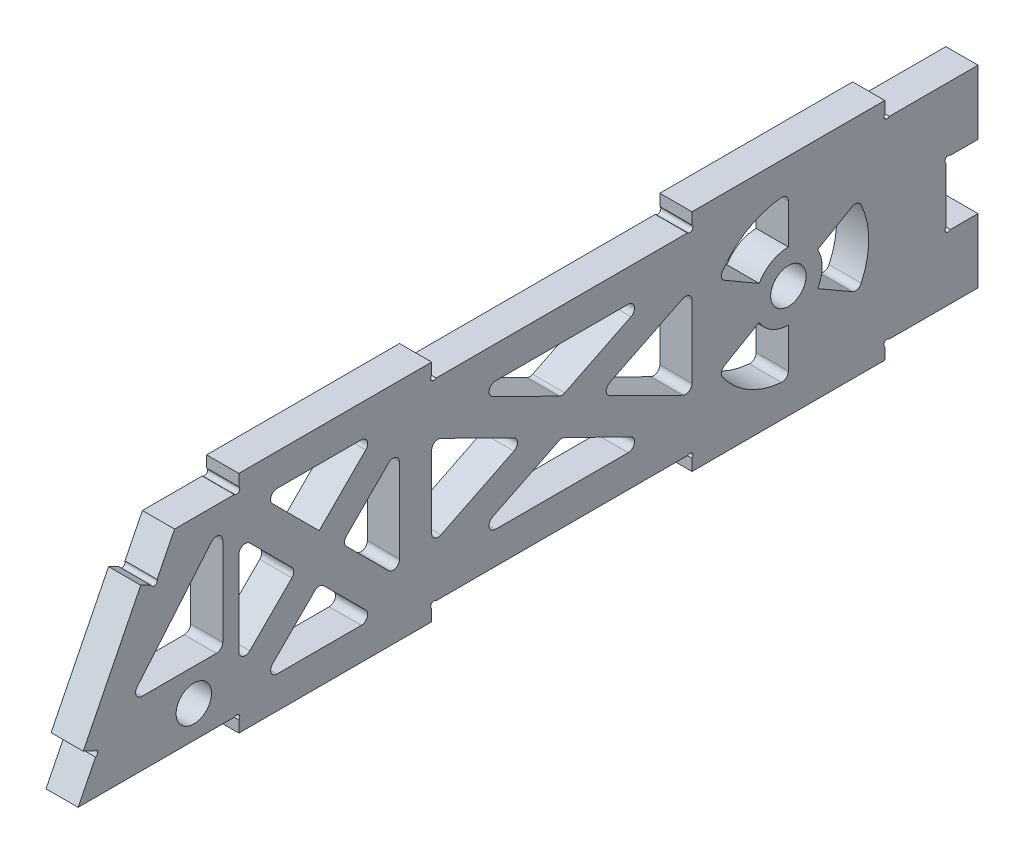
SolidWorks part; units mm, degrees
material "7050-T73510"
ref_plane "Front Plane" through (0, 0, 0) normal (0, 0, 1) x (1, 0, 0)
ref_plane "Top Plane" through (0, 0, 0) normal (0, 1, 0) x (1, 0, 0)
ref_plane "Right Plane" through (0, 0, 0) normal (1, 0, 0) x (0, 0, -1)
sketch "Sketch1" plane through (0, 0, 0) normal (1, 0, 0) x (0, 0, -1)
  line L1 (-177.8, -38.1) -> (177.8, -38.1)
  line L2 (-177.8, -38.1) -> (-177.8, 38.1)
  line L3 (-177.8, 38.1) -> (177.8, 38.1)
  line L4 (177.8, -38.1) -> (177.8, 38.1)
  line L5 (-177.8, -38.1) -> (177.8, 38.1) construction
  line L6 (-177.8, 38.1) -> (177.8, -38.1) construction
  point P0 (0, 0)
  dimension "D1" = 355.6
  dimension "D2" = 76.2
extrude "Boss-Extrude1" add sketch "Sketch1" along normal blind 12.7
sketch "Sketch2" plane through (12.7, 0, 0) normal (1, 0, 0) x (0, 0, -1)
  line L0 (-177.8, -38.1) -> (-139.7, 38.1)
  line L1 (177.8, 38.1) -> (-177.8, 38.1) construction
  dimension "D1" = 38.1
extrude "Cut-Extrude1" cut sketch "Sketch2" against normal through all and the other way through all
sketch "Sketch3" plane through (0, 0, 0) normal (-1, 0, 0) x (0, 0, 1)
  line L0 (177.8, -38.1) -> (-177.8, -38.1) construction
  line L1 (-140.97, -38.1) -> (-64.77, -38.1)
  line L2 (-140.97, -38.1) -> (-140.97, -44.45)
  line L3 (-140.97, -44.45) -> (-64.77, -44.45)
  line L4 (-64.77, -38.1) -> (-64.77, -44.45)
  line L5 (-177.8, -38.1) -> (-177.8, 38.1) construction
  line L6 (38.1, -38.1) -> (114.3, -38.1)
  line L7 (38.1, -38.1) -> (38.1, -44.45)
  line L8 (38.1, -44.45) -> (114.3, -44.45)
  line L9 (114.3, -38.1) -> (114.3, -44.45)
  line L10 (-177.8, 38.1) -> (139.7, 38.1) construction
  line L11 (-140.97, 38.1) -> (-64.77, 38.1)
  line L12 (-140.97, 38.1) -> (-140.97, 44.45)
  line L13 (-140.97, 44.45) -> (-64.77, 44.45)
  line L14 (-64.77, 38.1) -> (-64.77, 44.45)
  line L16 (38.1, 38.1) -> (114.3, 38.1)
  line L17 (38.1, 38.1) -> (38.1, 44.45)
  line L18 (38.1, 44.45) -> (114.3, 44.45)
  line L19 (114.3, 38.1) -> (114.3, 44.45)
  dimension "D1" = 76.2
  dimension "D2" = 6.35
  dimension "D3" = 76.2
  dimension "D4" = 6.35
  dimension "D5" = 36.83
  dimension "D6" = 215.9
  dimension "D7" = 76.2
  dimension "D8" = 6.35
  dimension "D9" = 6.35
  dimension "D10" = 76.2
extrude "Boss-Extrude2" add sketch "Sketch3" against normal blind 12.7
sketch "Sketch4" plane through (0, 0, 0) normal (-1, 0, 0) x (0, 0, 1)
  line L0 (-177.8, -38.1) -> (-177.8, 38.1) construction
  line L1 (-177.8, 12.7) -> (-165.1, 12.7)
  line L2 (-177.8, 12.7) -> (-177.8, -12.7)
  line L3 (-177.8, -12.7) -> (-165.1, -12.7)
  line L4 (-165.1, 12.7) -> (-165.1, -12.7)
  line L5 (-140.97, -38.1) -> (-177.8, -38.1) construction
  line L6 (-177.8, 38.1) -> (-140.97, 38.1) construction
  dimension "D1" = 25.4
  dimension "D2" = 25.4
  dimension "D3" = 12.7
extrude "Cut-Extrude2" cut sketch "Sketch4" against normal through all
sketch "Sketch5" plane through (0, 0, 0) normal (-1, 0, 0) x (0, 0, 1)
  line L0 (-165.1, -12.7) -> (-165.1, 12.7) construction
  line L1 (-140.97, -38.1) -> (-177.8, -38.1) construction
  circle A0 centre (-102.87, 0) radius 7
  dimension "D1" = 62.23
  dimension "D3" = 14
  dimension "D2" = 38.1
extrude "Cut-Extrude3" cut sketch "Sketch5" against normal through all
sketch "Sketch6" plane through (0, 0, 0) normal (-1, 0, 0) x (0, 0, 1)
  line L0 (38.1, -38.1) -> (-64.77, -38.1) construction
  line L1 (-64.77, 25.4) -> (38.1, 25.4)
  line L2 (-64.77, 25.4) -> (-64.77, -25.4)
  line L3 (-64.77, -25.4) -> (38.1, -25.4)
  line L4 (38.1, 25.4) -> (38.1, -25.4)
  line L5 (-64.77, 38.1) -> (38.1, 38.1) construction
  line L6 (38.1, 44.45) -> (38.1, 38.1) construction
  line L7 (-64.77, 38.1) -> (-64.77, 44.45) construction
  line L8 (-64.77, 25.4) -> (38.1, -25.4) construction
  line L9 (-64.77, -25.4) -> (38.1, 25.4) construction
  line L10 (-50.4288, -25.4) -> (-13.335, -7.0821)
  line L11 (23.7588, 25.4) -> (-13.335, 7.0821)
  line L12 (-50.4288, 25.4) -> (-13.335, 7.0821)
  line L13 (23.7588, -25.4) -> (-13.335, -7.0821)
  line L14 (1.0062, 0) -> (38.1, 18.3179)
  line L15 (-27.6762, 0) -> (-64.77, 18.3179)
  line L16 (1.0062, 0) -> (38.1, -18.3179)
  line L17 (-27.6762, 0) -> (-64.77, -18.3179)
  line L18 (38.1, -44.45) -> (114.3, -44.45) construction
  line L19 (50.8, 31.75) -> (114.3, 31.75)
  line L20 (50.8, 31.75) -> (50.8, -31.75)
  line L21 (50.8, -31.75) -> (114.3, -31.75)
  line L22 (114.3, 31.75) -> (114.3, -31.75)
  line L23 (114.3, 44.45) -> (38.1, 44.45) construction
  line L26 (114.3, 38.1) -> (114.3, 44.45) construction
  line L28 (50.8, -31.75) -> (114.3, 31.75) construction
  line L29 (114.3, -31.75) -> (50.8, 31.75) construction
  line L30 (59.7803, -31.75) -> (114.3, 22.7697)
  line L31 (50.8, -22.7697) -> (105.3197, 31.75)
  line L32 (114.3, -22.7697) -> (59.7803, 31.75)
  line L33 (105.3197, -31.75) -> (50.8, 22.7697)
  point P36 (114.3, 41.275)
  dimension "D1" = 12.7
  dimension "D2" = 12.7
  dimension "D3" = 12.7
  dimension "D4" = 12.7
  dimension "D5" = 12.7
  dimension "D6" = 12.7
  dimension "D7" = 12.7
  dimension "D8" = 0
  dimension "D9" = 12.7
  dimension "D10" = 12.7
extrude "Cut-Extrude4" cut sketch "Sketch6" against normal through all contours L3 L13 L10 | L17 L15 L2 | L1 L12 L11 | L14 L16 L4 | L21 L33 L30 | L32 L22 L30 | L31 L33 L20 | L32 L31 L19
sketch "Sketch8" plane through (12.7, 0, 0) normal (1, 0, 0) x (0, 0, -1)
  line L0 (-147.3908, 22.7185) -> (-170.1092, -22.7185)
  line L1 (-147.3908, 22.7185) -> (-153.0704, 25.5583)
  line L2 (-170.1092, -22.7185) -> (-175.7888, -19.8786)
  line L3 (-153.0704, 25.5583) -> (-175.7888, -19.8786)
  line L4 (-177.8, -38.1) -> (-139.7, 38.1) construction
  line L5 (-158.75, 0) -> (-181.9472, 11.5986) construction
  dimension "D1" = 6.35
  dimension "D2" = 50.8
extrude "Boss-Extrude3" add sketch "Sketch8" against normal blind 12.7
sketch "Sketch9" plane through (0, 0, 0) normal (-1, 0, 0) x (0, 0, 1)
  line L0 (147.3908, 22.7185) -> (147.7924, 23.9233) construction
  line L1 (170.1092, -22.7185) -> (172.0432, -23.3631) construction
  line L2 (147.3908, 22.7185) -> (153.0704, 25.5583) construction
  line L3 (175.7888, -19.8786) -> (170.1092, -22.7185) construction
  line L4 (-140.97, 38.1) -> (-141.868, 38.998) construction
  line L5 (37.202, -38.998) -> (38.1, -38.1) construction
  line L6 (38.1, -38.1) -> (-64.77, -38.1) construction
  line L7 (-63.872, -38.998) -> (-64.77, -38.1) construction
  line L8 (-141.868, -38.998) -> (-140.97, -38.1) construction
  line L9 (-140.97, -38.1) -> (-177.8, -38.1) construction
  line L10 (-165.998, -11.802) -> (-165.1, -12.7) construction
  line L11 (-165.1, -12.7) -> (-165.1, 12.7) construction
  line L12 (-165.998, 11.802) -> (-165.1, 12.7) construction
  line L13 (-165.1, 12.7) -> (-177.8, 12.7) construction
  line L14 (-140.97, 44.45) -> (-140.97, 38.1) construction
  line L15 (-63.872, 38.998) -> (-64.77, 38.1) construction
  line L16 (-64.77, 38.1) -> (-64.77, 44.45) construction
  line L17 (37.202, 38.998) -> (38.1, 38.1) construction
  line L18 (38.1, 44.45) -> (38.1, 38.1) construction
  line L19 (114.3, 38.1) -> (115.198, 38.998) construction
  line L20 (114.3, 38.1) -> (114.3, 44.45) construction
  line L21 (115.198, -38.998) -> (114.3, -38.1) construction
  line L22 (114.3, -44.45) -> (114.3, -38.1) construction
  circle A0 centre (-165.998, 11.802) radius 1.27
  circle A1 centre (-165.998, -11.802) radius 1.27
  circle A2 centre (-141.868, 38.998) radius 1.27
  circle A3 centre (-141.868, -38.998) radius 1.27
  circle A4 centre (-63.872, -38.998) radius 1.27
  circle A5 centre (-63.872, 38.998) radius 1.27
  circle A6 centre (37.202, 38.998) radius 1.27
  circle A7 centre (37.202, -38.998) radius 1.27
  circle A8 centre (115.198, -38.998) radius 1.27
  circle A9 centre (115.198, 38.998) radius 1.27
  circle A10 centre (147.7924, 23.9233) radius 1.27
  circle A11 centre (171.3141, -23.1201) radius 1.27
  dimension "D1" = 45
  dimension "D3" = 1.27
  dimension "D2" = 45
  dimension "D4" = 45
  dimension "D5" = 1.27
  dimension "D6" = 45
  dimension "D7" = 1.27
  dimension "D8" = 45
  dimension "D9" = 1.27
  dimension "D10" = 45
  dimension "D11" = 1.27
  dimension "D12" = 45
  dimension "D13" = 1.27
  dimension "D14" = 45
  dimension "D15" = 45
  dimension "D16" = 1.27
  dimension "D17" = 1.27
  dimension "D18" = 45
  dimension "D19" = 1.27
  dimension "D20" = 45
  dimension "D21" = 1.27
  dimension "D22" = 1.27
  dimension "D23" = 45
  dimension "D24" = 1.27
extrude "Cut-Extrude6" cut sketch "Sketch9" against normal through all
sketch "Sketch10" plane through (0, 0, 0) normal (-1, 0, 0) x (0, 0, 1)
  line L0 (-114.4314, -6.675) -> (-130.3663, -15.875)
  line L1 (-102.87, -13.35) -> (-102.87, -31.75)
  line L2 (-114.4314, 6.675) -> (-130.3663, 15.875)
  line L3 (-102.87, 13.35) -> (-102.87, 31.75)
  line L4 (-91.3086, 6.675) -> (-75.3737, 15.875)
  line L5 (-91.3086, -6.675) -> (-75.3737, -15.875)
  line L6 (120.65, -12.7) -> (158.0005, -12.7)
  line L7 (158.0005, -12.7) -> (120.65, 31.75)
  line L8 (120.65, -12.7) -> (120.65, 31.75)
  line L10 (177.8, -38.1) -> (116.0961, -38.1) construction
  line L11 (114.3, 22.7697) -> (114.3, -22.7697) construction
  line L13 (116.0961, 38.1) -> (139.7, 38.1) construction
  line L14 (153.0704, 25.5583) -> (175.7888, -19.8786) construction
  circle A0 centre (-102.87, 0) radius 13.35
  circle A1 centre (-102.87, 0) radius 7 construction
  circle A2 centre (-102.87, 0) radius 31.75
  point P21 (-102.87, 0)
  dimension "D1" = 6.35
  dimension "D2" = 63.5
  dimension "D4" = 25.4
  dimension "D5" = 6.35
  dimension "D6" = 6.35
  dimension "D7" = 12.7
  dimension "D3" = 6
extrude "Cut-Extrude7" cut sketch "Sketch10" against normal through all contours L2 A2 L0 A0 | L1 A2 L5 A0 | L4 A2 L3 A0 | L7 L8 L6
fillet "Fillet1" radius 2.54 6 edges at (6.35, 15.875, -75.3737) (6.35, 31.75, -102.87) (6.35, -31.75, -102.87) (6.35, -15.875, -75.3737) (6.35, 15.875, -130.3663) (6.35, -15.875, -130.3663)
fillet "Fillet2" radius 2.54 26 edges at (6.35, 18.3179, -64.77) (6.35, -18.3179, -64.77) (6.35, -25.4, -50.4288) (6.35, -25.4, 23.7588) (6.35, 0, -27.6762) (6.35, 0, 1.0062) (6.35, -7.0821, -13.335) (6.35, 18.3179, 38.1) (6.35, -18.3179, 38.1) (6.35, 7.0821, -13.335) (6.35, 25.4, 23.7588) (6.35, 25.4, -50.4288) (6.35, -31.75, 59.7803) (6.35, -31.75, 105.3197) (6.35, 22.7697, 50.8) (6.35, -22.7697, 50.8) (6.35, -22.7697, 114.3) (6.35, -8.9803, 82.55) (6.35, 22.7697, 114.3) (6.35, 0, 73.5697) (6.35, 31.75, 105.3197) (6.35, 0, 91.5303) (6.35, 31.75, 59.7803) (6.35, -12.7, 120.65) (6.35, -12.7, 158.0005) (6.35, 31.75, 120.65)
sketch "Sketch11" plane through (12.7, 0, 0) normal (1, 0, 0) x (0, 0, -1)
  line L0 (-177.8, -38.1) -> (-116.0961, -38.1) construction
  circle A0 centre (-132.08, -25.4) radius 7
  dimension "D3" = 14
  dimension "D1" = 12.7
  dimension "D2" = 45.72
extrude "Cut-Extrude8" cut sketch "Sketch11" against normal through all
